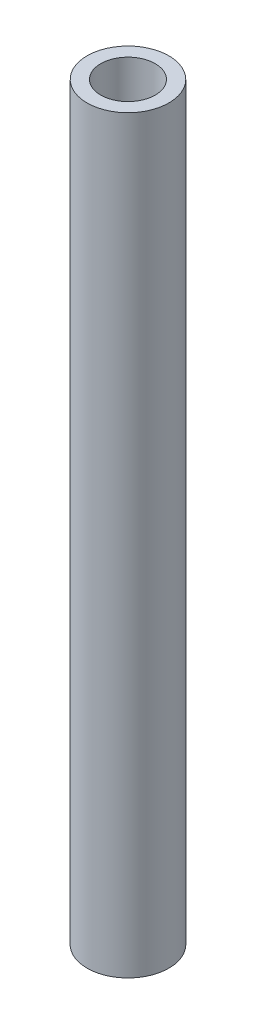
SolidWorks part; units mm, degrees
ref_plane "Front Plane" through (0, 0, 0) normal (0, 0, 1) x (1, 0, 0)
ref_plane "Top Plane" through (0, 0, 0) normal (0, 1, 0) x (1, 0, 0)
ref_plane "Right Plane" through (0, 0, 0) normal (1, 0, 0) x (0, 0, -1)
sketch "Sketch2" plane through (0, 0, 0) normal (0, 1, 0) x (1, 0, 0)
  circle A0 centre (0, 0) radius 3
  dimension "D1" = 6
extrude "Boss-Extrude1" add sketch "Sketch2" along normal blind 55
sketch "Sketch3" plane through (0, 55, 0) normal (0, 1, 0) x (1, 0, 0)
  circle A0 centre (0, 0) radius 2
  dimension "D1" = 4
extrude "Cut-Extrude1" cut sketch "Sketch3" against normal through all
